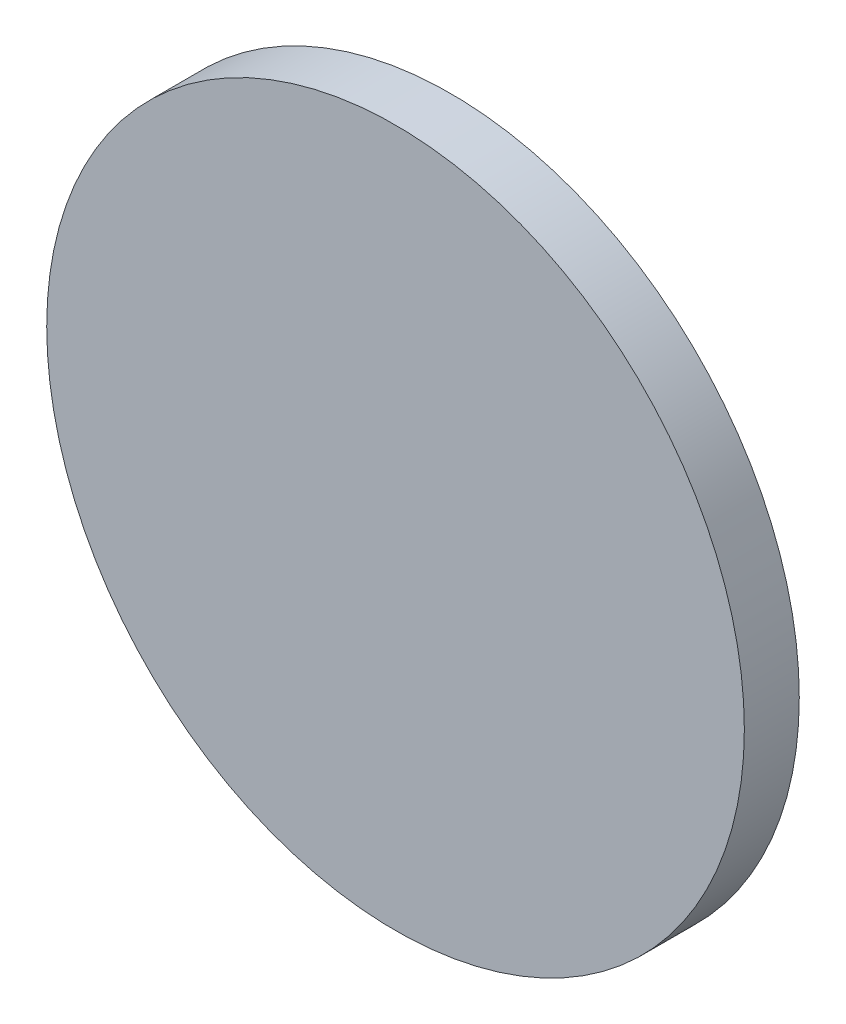
SolidWorks part; units mm, degrees
material "A-Glass Fiber"
ref_plane "Front Plane" through (0, 0, 0) normal (0, 0, 1) x (1, 0, 0)
ref_plane "Top Plane" through (0, 0, 0) normal (0, 1, 0) x (1, 0, 0)
ref_plane "Right Plane" through (0, 0, 0) normal (1, 0, 0) x (0, 0, -1)
ref_plane "Plane1"
sketch "Sketch1" plane through (0, 0, 0) normal (0, 0, 1) x (1, 0, 0)
  circle A0 centre (0, 0) radius 12.7
  dimension "D1" = 25.4
extrude "Extrusion1" add sketch "Sketch1" along normal blind 2
